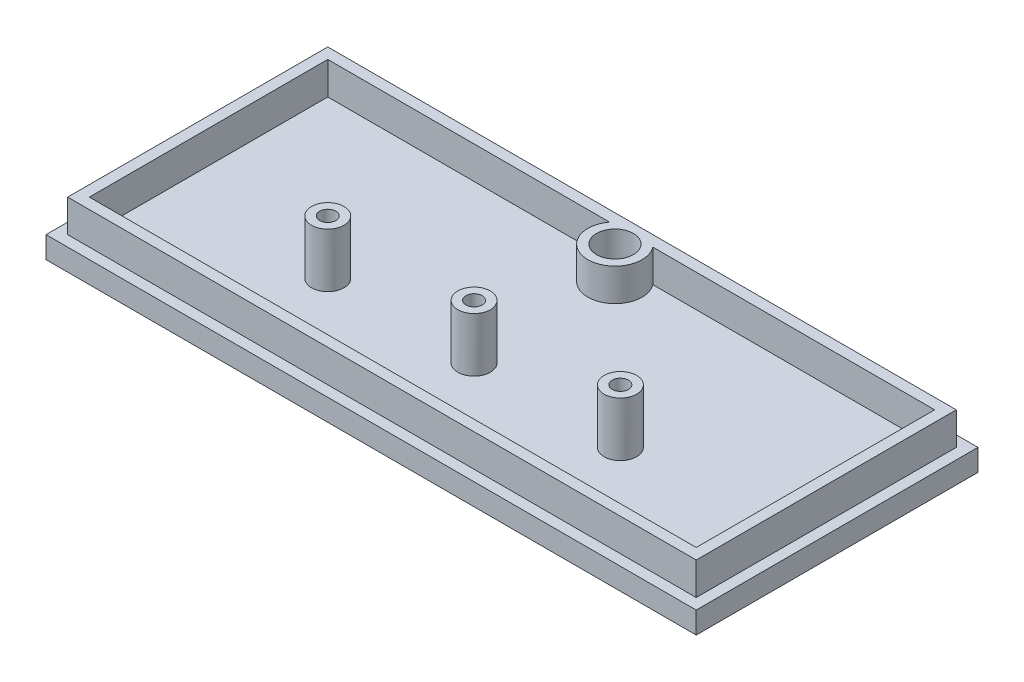
SolidWorks part; units mm, degrees
ref_plane "Front" through (0, 0, 0) normal (0, 0, 1) x (1, 0, 0)
ref_plane "Top" through (0, 0, 0) normal (0, 1, 0) x (1, 0, 0)
ref_plane "Right" through (0, 0, 0) normal (1, 0, 0) x (0, 0, -1)
sketch "Sketch1" plane through (0, 0, 0) normal (0, 1, 0) x (1, 0, 0)
  line L1 (0, 0) -> (60, 0)
  line L2 (0, 0) -> (0, 26)
  line L3 (0, 26) -> (60, 26)
  line L4 (60, 0) -> (60, 26)
  dimension "D1" = 26
  dimension "D2" = 60
extrude "Boss-Extrude1" add sketch "Sketch1" along normal blind 2
sketch "Sketch2" plane through (0, 2, 0) normal (0, 1, 0) x (1, 0, 0)
  line L0 (60, 26) -> (0, 26) construction
  line L1 (1, 25) -> (59, 25)
  line L2 (1, 25) -> (1, 1)
  line L3 (1, 1) -> (59, 1)
  line L4 (59, 25) -> (59, 1)
  line L5 (0, 26) -> (0, 0) construction
  line L6 (0, 0) -> (60, 0) construction
  line L7 (60, 0) -> (60, 26) construction
  line L9 (2, 24) -> (58, 24)
  line L10 (2, 24) -> (2, 2)
  line L11 (2, 2) -> (58, 2)
  line L12 (58, 24) -> (58, 2)
  dimension "D1" = 1
  dimension "D2" = 1
  dimension "D3" = 1
  dimension "D4" = 1
  dimension "D5" = 1
  dimension "D6" = 1
  dimension "D7" = 1
  dimension "D8" = 1
extrude "Boss-Extrude2" add sketch "Sketch2" along normal blind 3
sketch "Sketch3" plane through (0, 2, 0) normal (0, 1, 0) x (1, 0, 0)
  line L0 (2, 24) -> (2, 2) construction
  line L2 (2, 2) -> (58, 2) construction
  circle A0 centre (16.5, 9.5) radius 1.5
  circle A1 centre (30, 9.5) radius 1.5
  circle A2 centre (43.5, 9.5) radius 1.5
  circle A3 centre (16.5, 9.5) radius 0.75
  circle A4 centre (30, 9.5) radius 0.75
  circle A5 centre (43.5, 9.5) radius 0.75
  dimension "D1" = 3
  dimension "D2" = 3
  dimension "D3" = 3
  dimension "D8" = 1.5
  dimension "D9" = 1.5
  dimension "D10" = 1.5
  dimension "D4" = 14.5
  dimension "D5" = 13.5
  dimension "D6" = 13.5
  dimension "D7" = 7.5
extrude "Boss-Extrude3" add sketch "Sketch3" along normal blind 5
sketch "Sketch6" plane through (0, 2, 0) normal (0, 1, 0) x (1, 0, 0)
  line L0 (60, 26) -> (0, 26) construction
  line L1 (0, 26) -> (0, 0) construction
  circle A0 centre (30, 22.5) radius 2.5
  dimension "D3" = 5
  dimension "D1" = 3.5
  dimension "D2" = 30
extrude "Boss-Extrude4" add sketch "Sketch6" along normal blind 3
hole_wizard "CSK for M3 Flat Head Machine Screw1" positions "Sketch5" profile "Sketch4" countersink size "M3" standard "ANSI Metric" end condition through all
sketch "Sketch5" plane through (0, 0, 0) normal (0, -1, 0) x (-1, 0, 0)
  line L0 (-60, 26) -> (0, 26) construction
  line L1 (0, 26) -> (0, 0) construction
  point P0 (-30, 22.5)
  dimension "D1" = 3.5
  dimension "D2" = 30
sketch "Sketch4" plane through (30, 0, -22.5) normal (1, 0, 0) x (0, 0, -1)
  line L0 (0, 0) -> (0, 7)
  line L1 (0, 7) -> (1.7, 7)
  line L2 (1.7, 7) -> (1.7, 1.45)
  line L3 (1.7, 1.45) -> (3.15, 0)
  line L5 (3.15, 0) -> (0, 0)
  line L6 (-1.7, 1.45) -> (-3.15, 0) construction
  line L11 (0, -6.35) -> (0, 107.95) construction
  dimension "Thru Hole Dia." = 3.4
  dimension "Thru Hole Depth" = 7
  dimension "Near C'Sink Dia." = 6.3
  dimension "Near C'Sink Angle" = 90
